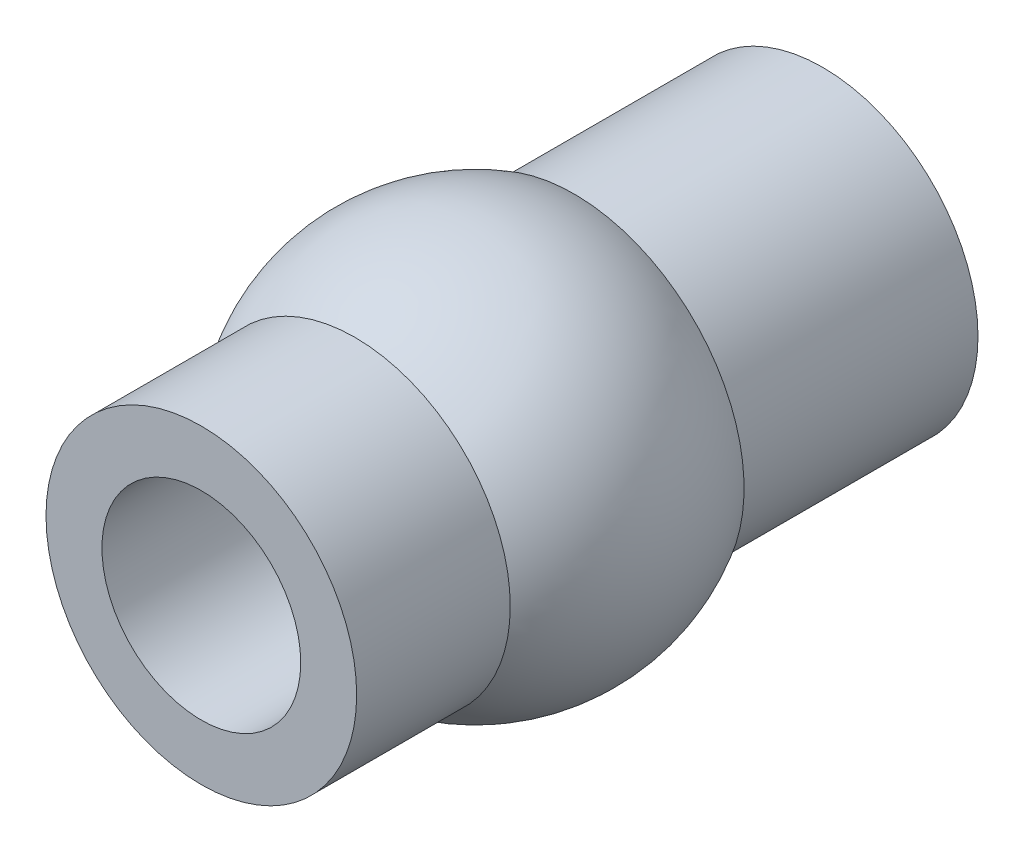
SolidWorks part; units mm, degrees
ref_plane "前视基准面" through (0, 0, 0) normal (0, 0, 1) x (1, 0, 0)
ref_plane "上视基准面" through (0, 0, 0) normal (0, 1, 0) x (1, 0, 0)
ref_plane "右视基准面" through (0, 0, 0) normal (1, 0, 0) x (0, 0, -1)
sketch "草图1" plane through (0, 0, 0) normal (0, 0, 1) x (1, 0, 0)
  circle A0 centre (0, 0) radius 2.5
  dimension "D1" = 5
extrude "凸台-拉伸1" add sketch "草图1" along normal blind 10
ref_plane "基准面1" through (0, 0, 8) normal (0, 0, 1) x (1, 0, 0)
sketch "草图2" plane through (0, 0, 0) normal (0, 1, 0) x (1, 0, 0)
  line L0 (0, -8) -> (0, 0) construction
  line L1 (-2.75, -8) -> (2.75, -8) construction
  line L2 (0, -8) -> (-2.049, -8)
  line L3 (0, -4) -> (-2.735, -4)
  line L4 (2.5, 0) -> (-2.5, 0) construction
  line L5 (0, -4) -> (0, -8)
  arc A0 (-2.735, -4) -> (-2.049, -8) centre (0, -5.5897) ccw
  dimension "D1" = 4
revolve "旋转1" add sketch "草图2" angle 360 about L0
sketch "草图3" plane through (0, 0, 10) normal (0, 0, 1) x (1, 0, 0)
  circle A0 centre (0, 0) radius 1.6
  dimension "D1" = 3.2
extrude "切除-拉伸1" cut sketch "草图3" against normal through all
